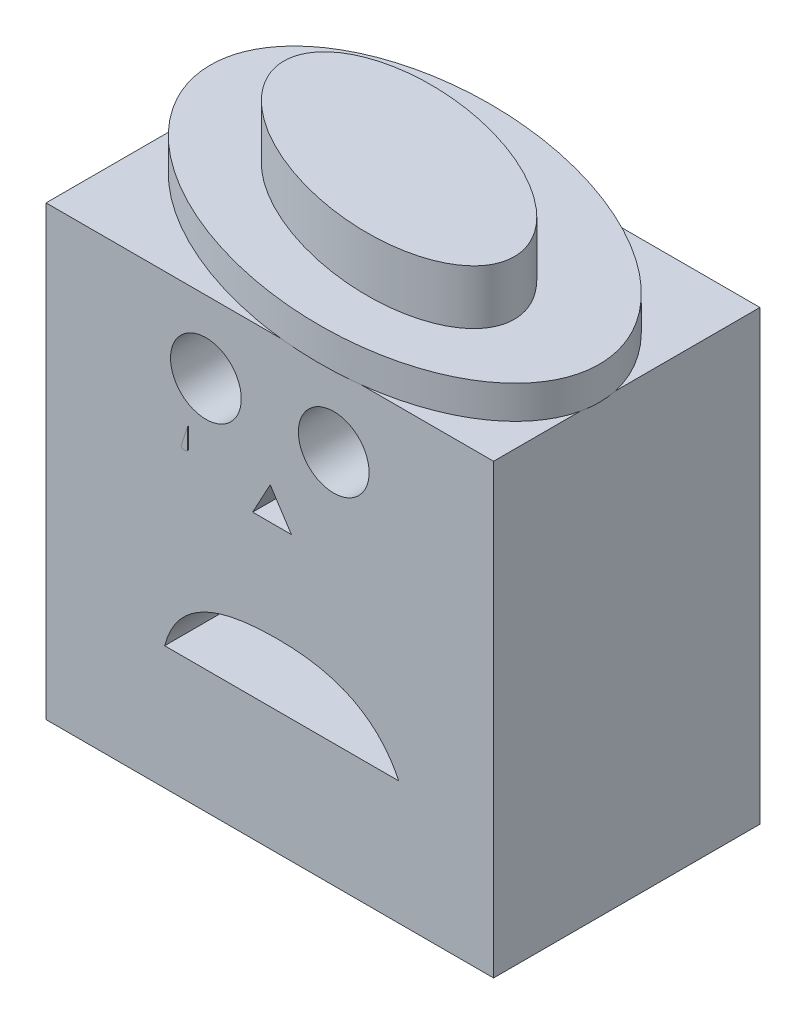
SolidWorks part; units mm, degrees
ref_plane "Front" through (0, 0, 0) normal (0, 0, 1) x (1, 0, 0)
ref_plane "Top" through (0, 0, 0) normal (0, 1, 0) x (1, 0, 0)
ref_plane "Right" through (0, 0, 0) normal (1, 0, 0) x (0, 0, -1)
sketch "Sketch1" plane through (0, 0, 0) normal (0, 0, 1) x (1, 0, 0)
  line L0 (-1256.277, 773.5044) -> (-836.277, 773.5044)
  line L1 (-1256.277, 773.5044) -> (-1256.277, 353.5044)
  line L2 (-836.277, 773.5044) -> (-836.277, 353.5044)
  line L3 (-1256.277, 353.5044) -> (-836.277, 353.5044)
  line L4 (-1045.8899, 649.5635) -> (-1062.402, 619.0797)
  line L5 (-1062.402, 619.0797) -> (-1045.8899, 649.5635)
  line L6 (-1026.0071, 619.0797) -> (-1062.402, 619.0797)
  line L7 (-1026.0071, 619.0797) -> (-1045.8899, 649.5635)
  line L8 (-1144.962, 469.2015) -> (-925.2252, 469.2015)
  circle A0 centre (-1106.277, 705.7924) radius 33.2031
  circle A1 centre (-986.277, 705.7924) radius 33.2031
  spline S0 degree 3 poles (-1144.962, 469.2015) (-1132.8348, 516.0554) (-1038.4469, 538.6229) (-948.5233, 517.6348) (-925.2252, 469.2015) knots 0 0 0 0 0.465701 1 1 1 1
  dimension "D3" = 120
  dimension "D1" = 420
  dimension "D2" = 420
  dimension "D4" = 150
extrude "Boss-Extrude2" add sketch "Sketch1" along normal blind 250 contours L1 L3 L2 L0 A1 A0 L7 L6 L4 L8 S0
sketch "Sketch2" plane through (0, 0, 250) normal (0, 0, 1) x (1, 0, 0)
  line L0 (-1122.4629, 659.2185) -> (-1128.5391, 640.4375)
  line L2 (-1122.4629, 640.0007) -> (-1122.4629, 659.2185)
  arc A0 (-1122.4629, 640.0007) -> (-1122.9799, 639.1251) centre (-1123.4629, 640.0007) cw
  arc A1 (-1128.5391, 640.4375) -> (-1128.1286, 639.2887) centre (-1127.5876, 640.1297) ccw
  spline S0 degree 3 poles (-1128.1286, 639.2887) (-1127.2903, 638.7494) (-1125.5823, 638.183) (-1123.8578, 638.6408) (-1122.9799, 639.1251) knots 0.103294 0.103294 0.103294 0.103294 0.511857 0.920053 0.920053 0.920053 0.920053
  dimension "D1" = 1
extrude "Boss-Extrude3" add sketch "Sketch2" along normal blind 1 contours L0 A1 S0 A0 L2
sketch "Sketch4" plane through (0, 773.5044, 0) normal (0, 1, 0) x (1, 0, 0)
  ellipse E0 centre (-1047.3561, -122.2046) end of major axis (-1258.6112, -76.4218) minor radius 124.4386
extrude "Boss-Extrude4" add sketch "Sketch4" along normal blind 31
sketch "Sketch5" plane through (0, 804.5044, 0) normal (0, 1, 0) x (1, 0, 0)
  ellipse E0 centre (-1044.4071, -130.5463) end of major axis (-911.9842, -164.9092) minor radius 69.0562
extrude "Boss-Extrude5" add sketch "Sketch5" along normal blind 51
